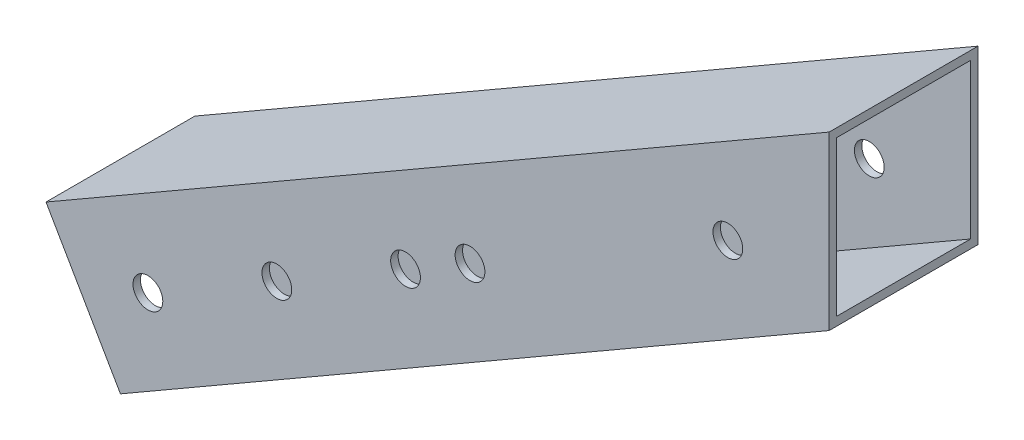
SolidWorks part; units mm, degrees
ref_plane "前视基准面" through (0, 0, 0) normal (0, 0, 1) x (1, 0, 0)
ref_plane "上视基准面" through (0, 0, 0) normal (0, 1, 0) x (1, 0, 0)
ref_plane "右视基准面" through (0, 0, 0) normal (1, 0, 0) x (0, 0, -1)
sketch "草图1" plane through (0, 0, 0) normal (0, 0, 1) x (1, 0, 0)
  line L0 (-47.7223, -23.7493) -> (-37.7223, -41.0698)
  line L1 (-37.7223, -41.0698) -> (57.4848, 13.898)
  line L2 (57.4848, 13.898) -> (57.4848, 36.992)
  line L3 (57.4848, 36.992) -> (-47.7223, -23.7493)
  circle A0 centre (43.8802, 17.5904) radius 2
  circle A1 centre (9.2392, -2.4096) radius 2
  circle A2 centre (0.5789, -7.4096) radius 2
  circle A3 centre (-16.7124, -17.4583) radius 2
  circle A4 centre (-34.0329, -27.4583) radius 2
extrude "凸台-拉伸1" add sketch "草图1" along normal blind 20
sketch "草图2" plane through (-46.0755, -26.6017, 0) normal (-0.866, -0.5, 0) x (0, 0, 1)
  line L0 (10, -16.7064) -> (10, 3.2936) construction
  line L1 (20, -16.7064) -> (0, -16.7064) construction
  line L2 (20, 3.2936) -> (0, 3.2936) construction
  line L4 (1, 2.2936) -> (19, 2.2936)
  line L5 (1, 2.2936) -> (1, -15.7064)
  line L6 (1, -15.7064) -> (19, -15.7064)
  line L7 (19, 2.2936) -> (19, -15.7064)
  line L8 (10, -15.7064) -> (10, 2.2936) construction
  line L9 (1, -6.7064) -> (19, -6.7064) construction
  point P6 (10, -6.7064)
  dimension "D1" = 18
  dimension "D2" = 18
extrude "切除-拉伸1" cut sketch "草图2" against normal through all
